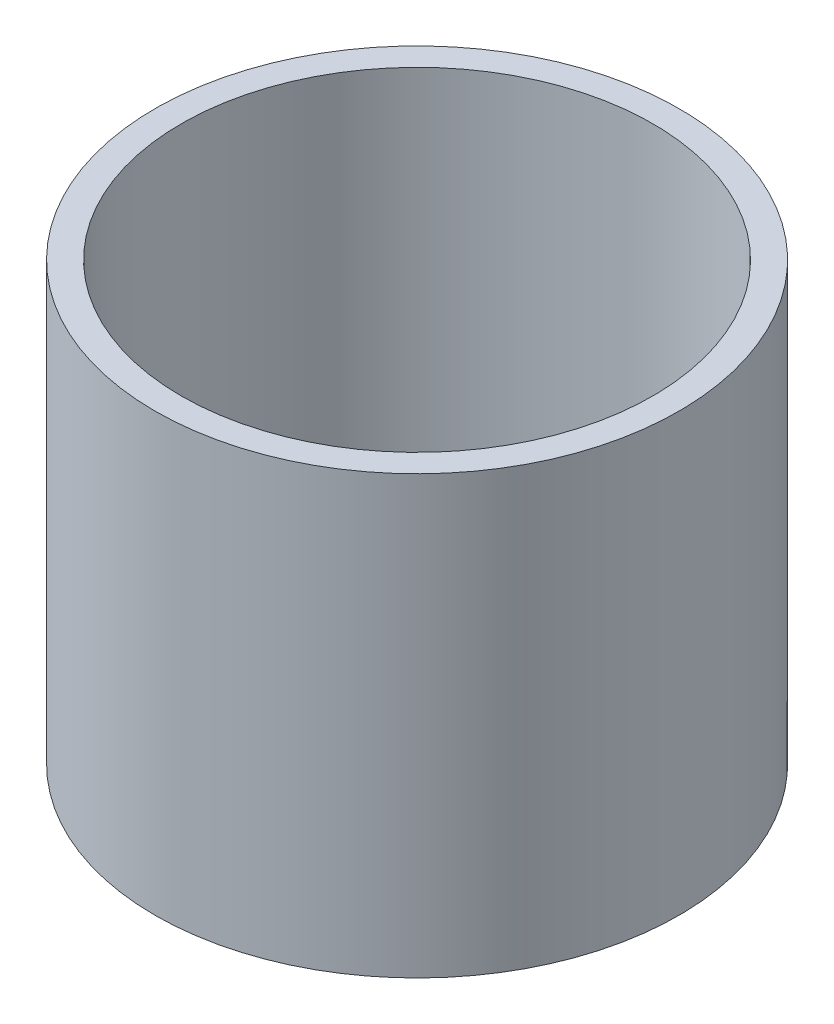
SolidWorks part; units mm, degrees
ref_plane "Front Plane" through (0, 0, 0) normal (0, 0, 1) x (1, 0, 0)
ref_plane "Top Plane" through (0, 0, 0) normal (0, 1, 0) x (1, 0, 0)
ref_plane "Right Plane" through (0, 0, 0) normal (1, 0, 0) x (0, 0, -1)
sketch "Sketch1" plane through (0, 0, 0) normal (0, 1, 0) x (1, 0, 0)
  circle A0 centre (-21.651, 19.0529) radius 30
extrude "Boss-Extrude1" add sketch "Sketch1" along normal blind 50
sketch "Sketch2" plane through (0, 50, 0) normal (0, 1, 0) x (1, 0, 0)
  circle A0 centre (-21.651, 19.0529) radius 27
extrude "Cut-Extrude1" cut sketch "Sketch2" against normal blind 47
